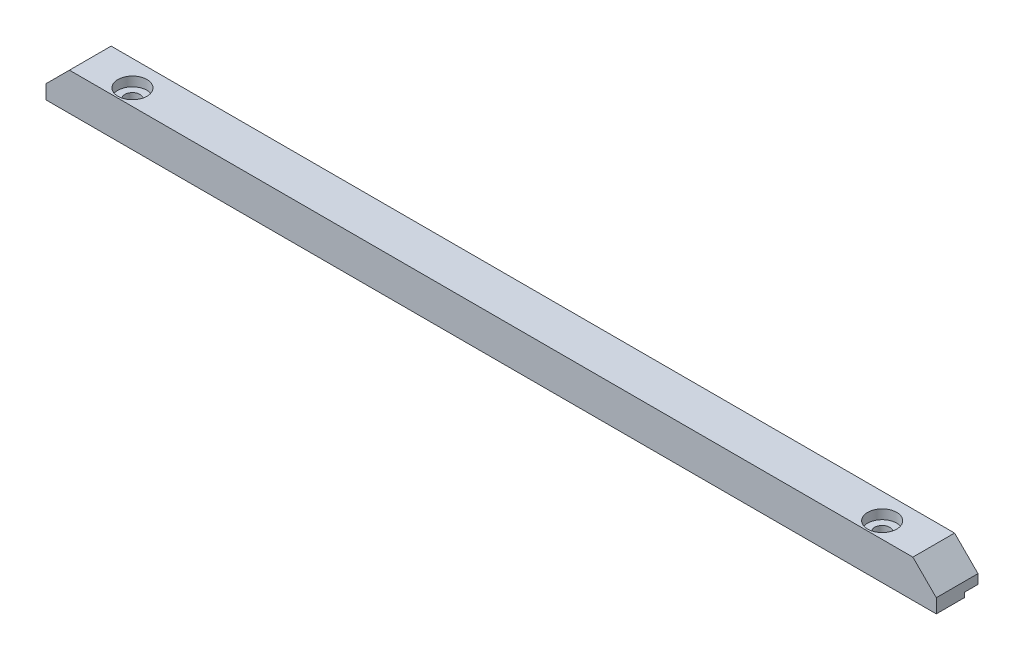
SolidWorks part; units mm, degrees
ref_plane "前视基准面" through (0, 0, 0) normal (0, 0, 1) x (1, 0, 0)
ref_plane "上视基准面" through (0, 0, 0) normal (0, 1, 0) x (1, 0, 0)
ref_plane "右视基准面" through (0, 0, 0) normal (1, 0, 0) x (0, 0, -1)
other "Configuration Table"
sketch "草图1" plane through (0, 0, 0) normal (0, 1, 0) x (1, 0, 0)
  line L1 (0, 0) -> (337.35, 0)
  line L2 (0, 0) -> (0, 116.87)
  line L3 (0, 116.87) -> (337.35, 116.87)
  line L4 (337.35, 0) -> (337.35, 116.87)
  line L5 (6.9, 109.97) -> (330.95, 109.97)
  line L6 (6.9, 109.97) -> (6.9, 6.9)
  line L7 (6.9, 6.9) -> (330.95, 6.9)
  line L8 (330.95, 109.97) -> (330.95, 6.9)
  dimension "D1" = 116.87
  dimension "D2" = 337.35
  dimension "D3" = 6.9
  dimension "D4" = 6.4
  dimension "D5" = 6.9
  dimension "D6" = 6.9
extrude "凸台-拉伸1" add sketch "草图1" along normal blind 8
fillet "圆角1" radius 5 4 edges at (0, 4, 0) (0, 4, -116.87) (337.35, 4, -116.87) (337.35, 4, 0)
sketch "草图2" plane through (0, 8, 0) normal (0, 1, 0) x (1, 0, 0)
  line L0 (167.17, 132.4281) -> (167.17, -13.3473) construction
  line L1 (0, 58.435) -> (337.35, 58.435) construction
  line L2 (0, 111.87) -> (0, 5) construction
  line L3 (337.35, 5) -> (337.35, 111.87) construction
  line L4 (23.7897, 113.42) -> (281.2218, 113.42) construction
  line L5 (3.45, 113.0437) -> (3.45, 3.45) construction
  line L6 (3.45, 3.45) -> (334.15, 3.45) construction
  line L7 (334.15, 3.45) -> (334.15, 110.0858) construction
  line L8 (332.35, 116.87) -> (5, 116.87) construction
  line L9 (330.95, 109.97) -> (6.9, 109.97) construction
  line L10 (6.9, 109.97) -> (6.9, 6.9) construction
  line L11 (6.9, 6.9) -> (330.95, 6.9) construction
  line L12 (5, 0) -> (332.35, 0) construction
  line L13 (330.95, 6.9) -> (330.95, 109.97) construction
  point P26 (87.17, 113.42)
  point P27 (247.17, 113.42)
  point P28 (247.17, 3.45)
  point P29 (87.17, 3.45)
  point P30 (3.45, 18.435)
  point P31 (334.15, 98.435)
  point P32 (3.45, 98.435)
  point P33 (334.15, 18.435)
  dimension "D1" = 167.17
  dimension "D2" = 160
  dimension "D3" = 80
hole_wizard "Ø3.2 (3.2) 直径孔1" positions "草图3" profile "草图4" hole size "Ø3.2" standard "ANSI Metric" end condition through all
sketch "草图3" plane through (0, 8, 0) normal (0, 1, 0) x (1, 0, 0)
  point P0 (3.45, 98.435)
  point P3 (87.17, 113.42)
  point P6 (247.17, 113.42)
  point P9 (334.15, 98.435)
  point P12 (334.15, 18.435)
  point P15 (247.17, 3.45)
  point P18 (87.17, 3.45)
  point P21 (3.45, 18.435)
sketch "草图4" plane through (3.45, 8, -98.435) normal (1, 0, 0) x (0, 0, 1)
  line L0 (0, 0) -> (0, 8)
  line L1 (0, 8) -> (1.6, 8)
  line L2 (1.6, 8) -> (1.6, 0)
  line L5 (1.6, 0) -> (0, 0)
  line L11 (0, -6.35) -> (0, 107.95) construction
  dimension "通孔孔直径" = 3.2
  dimension "通孔孔深度" = 8
sketch "草图5" plane through (0, 0, -109.97) normal (0, 0, 1) x (1, 0, 0)
  line L0 (330.95, 0) -> (6.9, 0) construction
  line L1 (41.9, 0) -> (73.9, 0)
  line L2 (41.9, 0) -> (41.9, 1.5)
  line L3 (41.9, 1.5) -> (73.9, 1.5)
  line L4 (73.9, 0) -> (73.9, 1.5)
  line L5 (6.9, 8) -> (6.9, 0) construction
  dimension "D1" = 35
  dimension "D2" = 32
  dimension "D3" = 1.5
extrude "切除-拉伸1" cut sketch "草图5" against normal through all
sketch "草图6" plane through (0, 0, -109.97) normal (0, 0, 1) x (1, 0, 0)
  line L0 (330.95, 8) -> (6.9, 8) construction
  line L1 (41.9, 0) -> (38.9, 0)
  line L2 (41.9, 0) -> (41.9, 8)
  line L3 (41.9, 8) -> (38.9, 8)
  line L4 (38.9, 0) -> (38.9, 8)
  dimension "D1" = 3
extrude "凸台-拉伸2" add sketch "草图6" along normal up to next
sketch "草图7" plane through (0, 0, -109.97) normal (0, 0, 1) x (1, 0, 0)
  line L1 (73.9, 0) -> (330.95, 0)
  line L2 (73.9, 0) -> (73.9, 8)
  line L3 (73.9, 8) -> (330.95, 8)
  line L4 (330.95, 0) -> (330.95, 8)
extrude "凸台-拉伸3" add sketch "草图7" along normal blind 4
sketch "草图8" plane through (0, 0, 0) normal (0, -1, 0) x (1, 0, 0)
  line L1 (330.95, -105.97) -> (73.9, -105.97)
  line L2 (330.95, -105.97) -> (330.95, -109.97)
  line L3 (330.95, -109.97) -> (73.9, -109.97)
  line L4 (73.9, -105.97) -> (73.9, -109.97)
extrude "凸台-拉伸4" add sketch "草图8" along normal blind 3
sketch "草图9" plane through (0, 8, 0) normal (0, 1, 0) x (1, 0, 0)
  circle A0 centre (137.8085, 107.33) radius 3.5
  circle A1 centre (328.3085, 74.31) radius 3.5
  circle A2 centre (328.3085, 13.35) radius 3.5
  circle A3 centre (262.2685, 9.54) radius 3.5
  circle A4 centre (92.0885, 9.54) radius 3.5
  circle A5 centre (22.2385, 9.54) radius 3.5
  circle A6 centre (9.5385, 23.51) radius 3.5
  circle A7 centre (9.5385, 103.52) radius 3.5
  dimension "D1" = 7
sketch "草图11" plane through (330.95, 0, 0) normal (-1, 0, 0) x (0, 0, 1)
  line L1 (-6.9, 8) -> (-105.97, 8)
  line L2 (-6.9, 8) -> (-6.9, -3)
  line L3 (-6.9, -3) -> (-105.97, -3)
  line L4 (-105.97, 8) -> (-105.97, -3)
extrude "凸台-拉伸5" add sketch "草图11" along normal blind 2
sketch "草图13" plane through (0, 0, -105.97) normal (0, 0, 1) x (1, 0, 0)
  line L0 (328.95, 8) -> (73.9, 8) construction
  line L1 (328.95, -3) -> (286.95, -3)
  line L2 (328.95, -3) -> (328.95, 1.5)
  line L3 (328.95, 1.5) -> (286.95, 1.5)
  line L4 (286.95, -3) -> (286.95, 1.5)
  dimension "D1" = 6.5
  dimension "D2" = 42
extrude "切除-拉伸2" cut sketch "草图13" against normal through all
sketch "草图14" plane through (0, 0, -6.9) normal (0, 0, -1) x (-1, 0, 0)
  line L0 (-41.9, 0) -> (-328.95, 0) construction
  line L1 (-233.95, 0) -> (-112.45, 0)
  line L2 (-233.95, 0) -> (-233.95, 1.5)
  line L3 (-233.95, 1.5) -> (-112.45, 1.5)
  line L4 (-112.45, 0) -> (-112.45, 1.5)
  line L6 (-41.9, 8) -> (-328.95, 8) construction
  line L7 (-328.95, 0) -> (-328.95, 8) construction
  dimension "D1" = 6.5
  dimension "D2" = 95
  dimension "D3" = 216.5
extrude "切除-拉伸3" cut sketch "草图14" against normal through all
sketch "草图16" plane through (0, 0, -109.97) normal (0, 0, 1) x (1, 0, 0)
  line L1 (41.9, 8) -> (73.9, 8)
  line L2 (41.9, 8) -> (41.9, 1.5)
  line L3 (41.9, 1.5) -> (73.9, 1.5)
  line L4 (73.9, 8) -> (73.9, 1.5)
extrude "凸台-拉伸7" add sketch "草图16" along normal up to surface (4 mm away)
sketch "草图17" plane through (330.95, 0, 0) normal (1, 0, 0) x (0, 0, -1)
  line L8 (109.97, -3) -> (109.97, 0)
  line L9 (109.97, 0) -> (6.9, 0)
  line L10 (6.9, 0) -> (6.9, -3)
  line L11 (6.9, -3) -> (109.97, -3)
  line L12 (109.97, -3) -> (109.97, 0)
  line L13 (109.97, 0) -> (6.9, 0)
  line L14 (6.9, 0) -> (6.9, -3)
  line L15 (6.9, -3) -> (109.97, -3)
  dimension "D1" = 0
extrude "切除-拉伸4" cut sketch "草图17" against normal blind 0.1
sketch "草图18" plane through (0, 0, -6.9) normal (0, 0, -1) x (-1, 0, 0)
  line L16 (-233.95, 0) -> (-233.95, 1.5)
  line L17 (-233.95, 1.5) -> (-112.45, 1.5)
  line L18 (-112.45, 1.5) -> (-112.45, 0)
  line L19 (-112.45, 0) -> (-41.9, 0)
  line L20 (-41.9, 0) -> (-41.9, 8)
  line L21 (-41.9, 8) -> (-328.95, 8)
  line L22 (-328.95, 8) -> (-328.95, 0)
  line L23 (-328.95, 0) -> (-233.95, 0)
  line L24 (-233.95, 0) -> (-233.95, 1.5)
  line L25 (-233.95, 1.5) -> (-112.45, 1.5)
  line L26 (-112.45, 1.5) -> (-112.45, 0)
  line L27 (-112.45, 0) -> (-41.9, 0)
  line L28 (-41.9, 0) -> (-41.9, 8)
  line L29 (-41.9, 8) -> (-328.95, 8)
  line L30 (-328.95, 8) -> (-328.95, 0)
  line L31 (-328.95, 0) -> (-233.95, 0)
  dimension "D1" = 0
extrude "凸台-拉伸8" add sketch "草图18" along normal blind 2
sketch "草图19" plane through (0, 0, 0) normal (0, -1, 0) x (1, 0, 0)
  line L0 (112.45, 0) -> (112.45, -8.9) construction
  line L1 (41.9, -8.9) -> (112.45, -8.9)
  line L2 (41.9, -8.9) -> (41.9, -6.9)
  line L3 (41.9, -6.9) -> (112.45, -6.9)
  line L4 (112.45, -8.9) -> (112.45, -6.9)
  line L6 (233.95, -8.9) -> (328.95, -8.9)
  line L7 (233.95, -8.9) -> (233.95, -6.9)
  line L8 (233.95, -6.9) -> (328.95, -6.9)
  line L9 (328.95, -8.9) -> (328.95, -6.9)
  dimension "D1" = 2
extrude "凸台-拉伸9" add sketch "草图19" along normal up to surface (3 mm away) up to face at (329.9, -3, -58.435)
sketch "草图10" plane through (0, -3, 0) normal (0, -1, 0) x (1, 0, 0)
  circle A2 centre (137.8085, -107.33) radius 3.5
  circle A3 centre (137.8085, -107.33) radius 3.5
  dimension "D1" = 0
sketch "草图20" plane through (0, -3, 0) normal (0, -1, 0) x (1, 0, 0)
  circle A58 centre (92.0885, -9.54) radius 3.5
  circle A59 centre (92.0885, -9.54) radius 3.5
  circle A120 centre (262.2685, -9.54) radius 3.5
  circle A121 centre (262.2685, -9.54) radius 3.5
  circle A123 centre (328.3085, -13.35) radius 3.5
  circle A124 centre (328.3085, -13.35) radius 3.5
  circle A126 centre (328.3085, -74.31) radius 3.5
  circle A127 centre (328.3085, -74.31) radius 3.5
  circle A129 centre (137.8085, -107.33) radius 3.5
  circle A130 centre (137.8085, -107.33) radius 3.5
  circle A132 centre (22.2385, -9.54) radius 3.5
  circle A133 centre (22.2385, -9.54) radius 3.5
  circle A135 centre (9.5385, -23.51) radius 3.5
  circle A136 centre (9.5385, -23.51) radius 3.5
  circle A138 centre (9.5385, -103.52) radius 3.5
  circle A139 centre (9.5385, -103.52) radius 3.5
  dimension "D1" = 0
  dimension "D2" = 0
  dimension "D3" = 0
  dimension "D4" = 0
  dimension "D5" = 0
  dimension "D6" = 0
  dimension "D7" = 0
  dimension "D8" = 0
extrude "切除-拉伸5" cut sketch "草图20" against normal blind 4
sketch "草图21" plane through (0, 8, 0) normal (0, 1, 0) x (1, 0, 0)
  circle A2 centre (87.17, 113.42) radius 3.1
  circle A3 centre (87.17, 113.42) radius 3.1
  circle A5 centre (247.17, 113.42) radius 3.1
  circle A6 centre (247.17, 113.42) radius 3.1
  circle A8 centre (334.15, 98.435) radius 3.1
  circle A9 centre (334.15, 98.435) radius 3.1
  circle A11 centre (334.15, 18.435) radius 3.1
  circle A12 centre (334.15, 18.435) radius 3.1
  circle A14 centre (247.17, 3.45) radius 3.1
  circle A15 centre (247.17, 3.45) radius 3.1
  circle A17 centre (87.17, 3.45) radius 3.1
  circle A18 centre (87.17, 3.45) radius 3.1
  circle A20 centre (3.45, 18.435) radius 3.1
  circle A21 centre (3.45, 18.435) radius 3.1
  circle A23 centre (3.45, 98.435) radius 3.1
  circle A24 centre (3.45, 98.435) radius 3.1
  dimension "D1" = 1.5
  dimension "D2" = 1.5
  dimension "D3" = 1.5
  dimension "D4" = 1.5
  dimension "D5" = 1.5
  dimension "D6" = 1.5
  dimension "D7" = 1.5
  dimension "D8" = 1.5
extrude "切除-拉伸6" cut sketch "草图21" against normal blind 2
ref_plane "基准面1" through (0, 4, 0) normal (0, 1, 0) x (1, 0, 0)
sketch "草图22" plane through (0, 4, 0) normal (0, 1, 0) x (1, 0, 0)
  line L0 (6.9, 106.97) -> (12.9, 106.97) construction
  line L1 (6.9, 109.97) -> (12.9, 109.97)
  line L2 (6.9, 109.97) -> (6.9, 103.97)
  line L3 (6.9, 103.97) -> (12.9, 103.97)
  line L4 (12.9, 109.97) -> (12.9, 103.97)
  line L5 (38.9, 109.97) -> (32.9, 109.97)
  line L6 (38.9, 109.97) -> (38.9, 103.97)
  line L7 (38.9, 103.97) -> (32.9, 103.97)
  line L8 (32.9, 109.97) -> (32.9, 103.97)
  line L9 (6.9, 6.9) -> (12.9, 6.9)
  line L10 (6.9, 6.9) -> (6.9, 12.9)
  line L11 (6.9, 12.9) -> (12.9, 12.9)
  line L12 (12.9, 6.9) -> (12.9, 12.9)
  line L13 (38.9, 6.9) -> (32.9, 6.9)
  line L14 (38.9, 6.9) -> (38.9, 12.9)
  line L15 (38.9, 12.9) -> (32.9, 12.9)
  line L16 (32.9, 6.9) -> (32.9, 12.9)
  line L17 (32.9, 106.97) -> (38.9, 106.97) construction
  line L18 (6.9, 9.9) -> (12.9, 9.9) construction
  line L19 (32.9, 9.9) -> (38.9, 9.9) construction
  circle A0 centre (9.9, 106.97) radius 1.5
  circle A1 centre (35.9, 106.97) radius 1.5
  circle A2 centre (9.9, 9.9) radius 1.5
  circle A3 centre (35.9, 9.9) radius 1.5
  dimension "D2" = 3
  dimension "D1" = 6
extrude "凸台-拉伸10" add sketch "草图22" along normal offset from surface 2 and the other way offset from surface (3 mm away) 1 up to face at (3.45, 8, -95.335) other way up to face at (16.1954, 0, -50.074)
sketch "草图23" plane through (0, 0, 0) normal (-1, 0, 0) x (0, 0, 1)
  line L0 (-111.87, 0) -> (-5, 0) construction
  line L1 (-58.435, 0) -> (-43.435, 0)
  line L2 (-58.435, 0) -> (-58.435, 1.5)
  line L3 (-58.435, 1.5) -> (-43.435, 1.5)
  line L4 (-43.435, 0) -> (-43.435, 1.5)
  line L6 (-58.435, 0) -> (-68.435, 0)
  line L7 (-58.435, 0) -> (-58.435, 1.5)
  line L8 (-58.435, 1.5) -> (-68.435, 1.5)
  line L9 (-68.435, 0) -> (-68.435, 1.5)
  line M9 (-111.87, 0) -> (-5, 0)
  dimension "D1" = 1.5
  dimension "D2" = 15
  dimension "D3" = 10
extrude "切除-拉伸7" cut sketch "草图23" against normal up to surface (6.9 mm away) contours L9 L2 L8 M9 | L4 L3 L2 M9 up to face at (6.9, 2.875, -48.61)
sketch "草图24" plane through (337.35, 0, 0) normal (1, 0, 0) x (0, 0, -1)
  line L1 (6.9, 0) -> (109.97, 0)
  line L2 (6.9, 0) -> (6.9, -3)
  line L3 (6.9, -3) -> (109.97, -3)
  line L4 (109.97, 0) -> (109.97, -3)
extrude "切除-拉伸8" cut sketch "草图24" against normal through all
sketch "草图25" plane through (0, 8, 0) normal (0, 1, 0) x (1, 0, 0)
  line L1 (72.17, 30.6891) -> (262.17, 30.6891)
  line L2 (72.17, 30.6891) -> (72.17, -18.2753)
  line L3 (72.17, -18.2753) -> (262.17, -18.2753)
  line L4 (262.17, 30.6891) -> (262.17, -18.2753)
  line L5 (368.6606, -45.0751) -> (-34.1079, -45.0751)
  line L6 (368.6606, -45.0751) -> (368.6606, 147.0076)
  line L7 (368.6606, 147.0076) -> (-34.1079, 147.0076)
  line L8 (-34.1079, -45.0751) -> (-34.1079, 147.0076)
  dimension "D1" = 15
  dimension "D2" = 15
extrude "切除-拉伸9" cut sketch "草图25" against normal through all
chamfer "倒角1" distance 5 angle 45 2 edges at (262.17, 8, -4.45) (72.17, 8, -4.45)
sketch "草图26" plane through (0, 1.5, 0) normal (0, -1, 0) x (1, 0, 0)
  line L4 (112.45, 0) -> (112.45, -8.9)
  line L5 (112.45, -8.9) -> (233.95, -8.9)
  line L6 (233.95, -8.9) -> (233.95, 0)
  line L7 (233.95, 0) -> (112.45, 0)
  line L8 (112.45, 0) -> (112.45, -8.9)
  line L9 (112.45, -8.9) -> (233.95, -8.9)
  line L10 (233.95, -8.9) -> (233.95, 0)
  line L11 (233.95, 0) -> (112.45, 0)
  dimension "D1" = 0
extrude "凸台-拉伸11" add sketch "草图26" along normal up to surface (1.5 mm away) up to face at (87.17, 0, -1.85)
